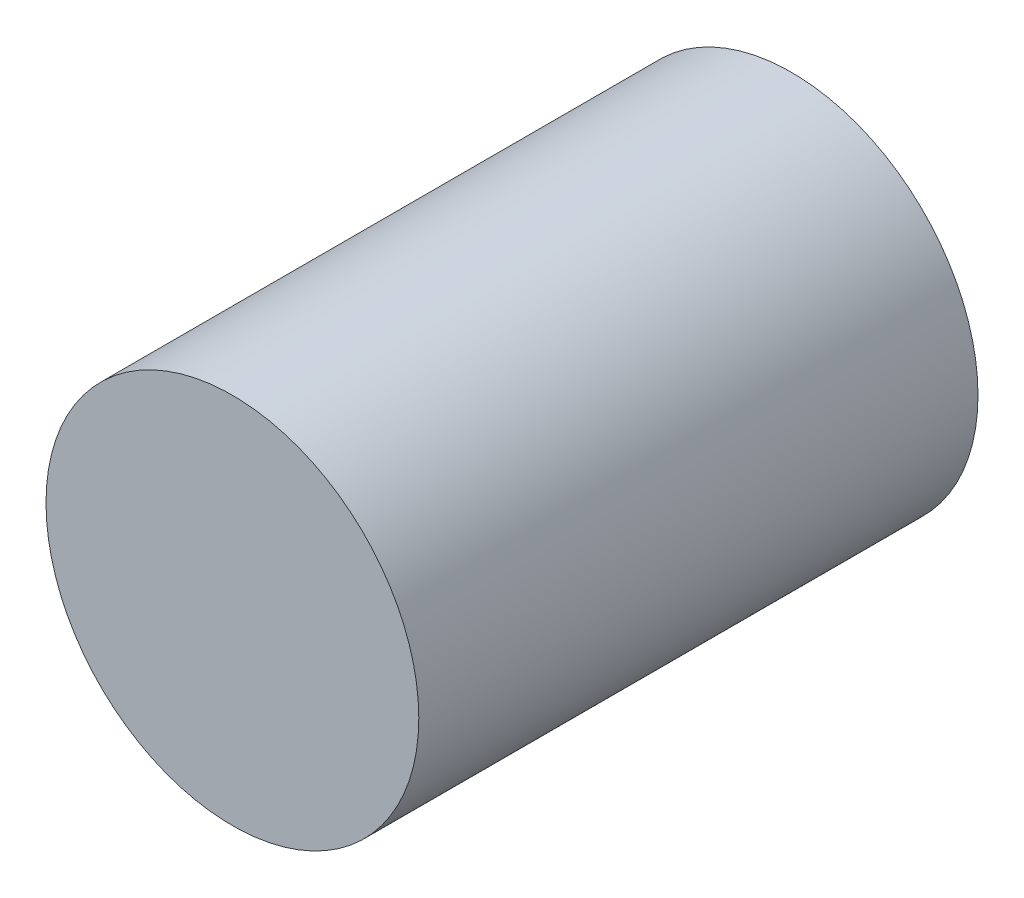
SolidWorks part; units mm, degrees
material "6061-T6 (SS)"
ref_plane "Front Plane" through (0, 0, 0) normal (0, 0, 1) x (1, 0, 0)
ref_plane "Top Plane" through (0, 0, 0) normal (0, 1, 0) x (1, 0, 0)
ref_plane "Right Plane" through (0, 0, 0) normal (1, 0, 0) x (0, 0, -1)
sketch "Sketch1" plane through (0, 0, 0) normal (0, 0, 1) x (1, 0, 0)
  circle A0 centre (0, 0) radius 6.35
extrude "Boss-Extrude1" add sketch "Sketch1" along normal blind 19.05
